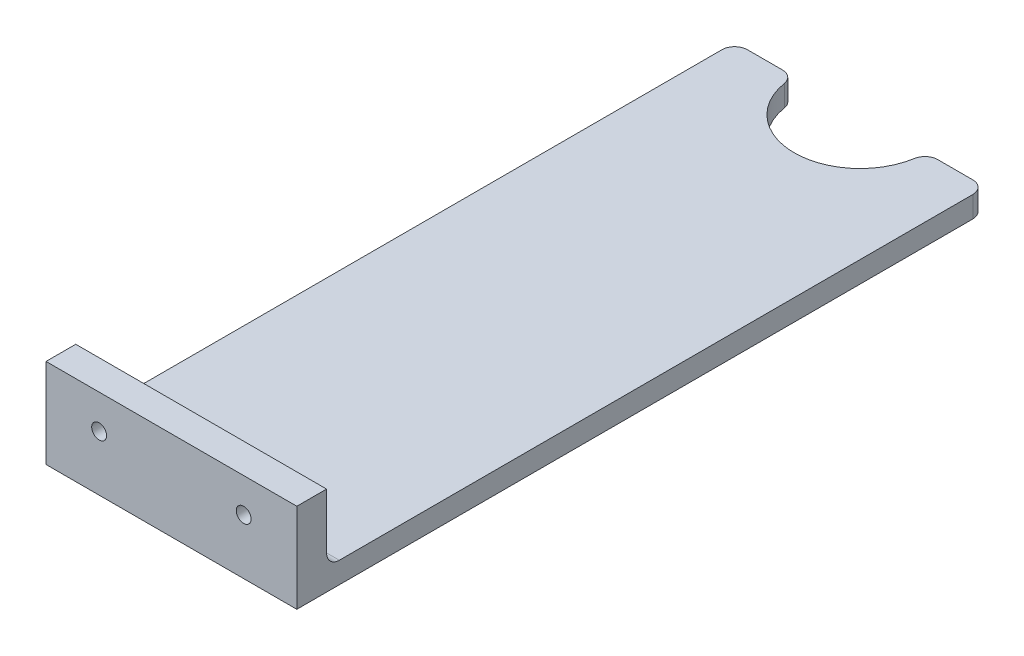
SolidWorks part; units mm, degrees
ref_plane "Front Plane" through (0, 0, 0) normal (0, 0, 1) x (1, 0, 0)
ref_plane "Top Plane" through (0, 0, 0) normal (0, 1, 0) x (1, 0, 0)
ref_plane "Right Plane" through (0, 0, 0) normal (1, 0, 0) x (0, 0, -1)
sketch "Sketch1" plane through (0, 0, 0) normal (0, 0, 1) x (1, 0, 0)
  line L1 (-29.5, -13) -> (29.5, -13)
  line L2 (-29.5, -13) -> (-29.5, 8)
  line L3 (-29.5, 8) -> (29.5, 8)
  line L4 (29.5, -13) -> (29.5, 8)
  circle A0 centre (-17, 0) radius 1.75
  circle A1 centre (17, 0) radius 1.75
  point P0 (0, 0)
  point P10 (0, 0)
  point P11 (0, 0)
  dimension "D1" = 3.5
  dimension "D2" = 3.5
  dimension "D3" = 17
  dimension "D4" = 17
  dimension "D5" = 29.5
  dimension "D6" = 29.5
  dimension "D7" = 8
  dimension "D8" = 13
extrude "Boss-Extrude1" add sketch "Sketch1" along normal blind 7
sketch "Sketch2" plane through (0, 0, 0) normal (0, 0, -1) x (-1, 0, 0)
  line L0 (29.5, 8) -> (29.5, -13) construction
  line L1 (-29.5, -13) -> (29.5, -13)
  line L2 (-29.5, -13) -> (-29.5, -8)
  line L3 (-29.5, -8) -> (29.5, -8)
  line L4 (29.5, -13) -> (29.5, -8)
  dimension "D1" = 5
extrude "Boss-Extrude2" add sketch "Sketch2" along normal blind 155
sketch "Sketch4" plane through (0, -8, 0) normal (0, 1, 0) x (1, 0, 0)
  line L0 (-29.5, 155) -> (29.5, 155) construction
  line L1 (-15.5, 155) -> (15.5, 155)
  arc A0 (-15.5, 155) -> (15.5, 155) centre (0, 155) ccw
  dimension "D1" = 15.5
extrude "Cut-Extrude1" cut sketch "Sketch4" against normal through all
fillet "Fillet1" radius 3 1 edges at (0, -8, 0)
fillet "Fillet2" radius 3 4 edges at (-29.5, -10.5, -155) (29.5, -10.5, -155) (15.5, -10.5, -155) (-15.5, -10.5, -155)
